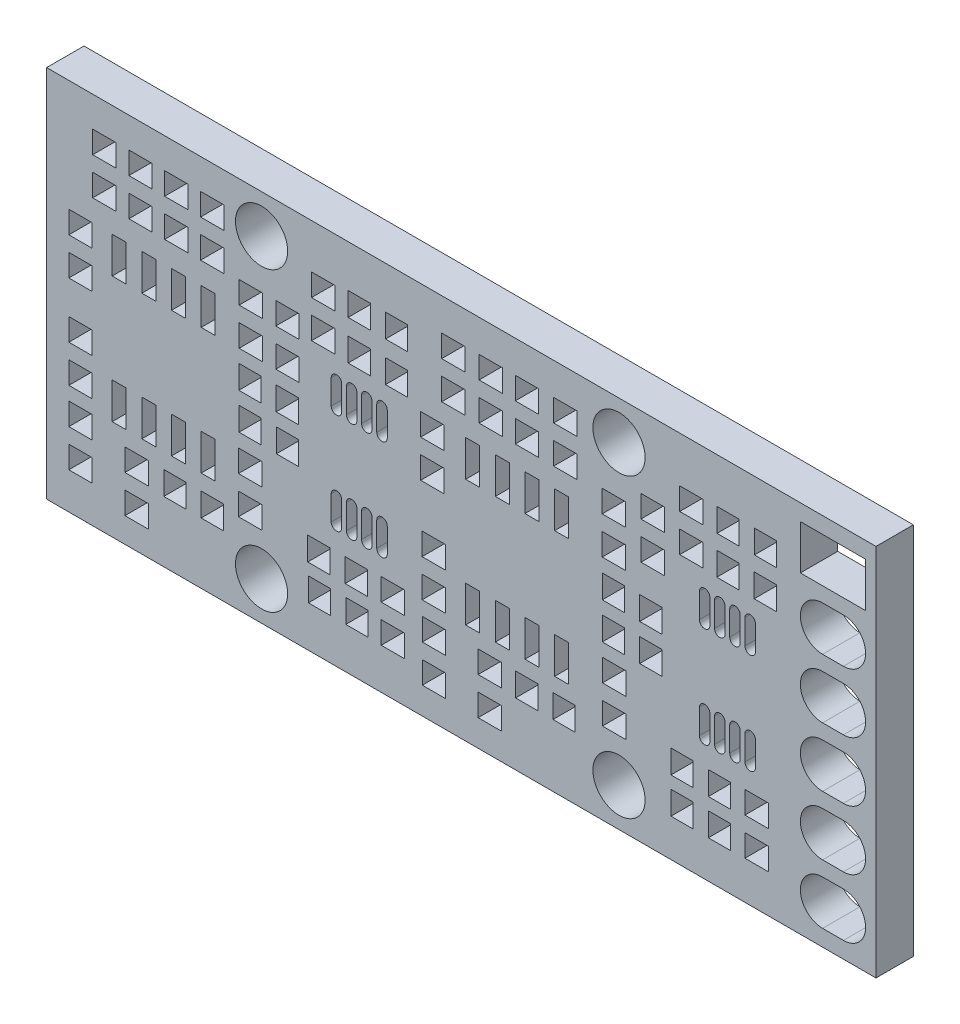
SolidWorks part; units mm, degrees
ref_plane "Plan de face" through (0, 0, 0) normal (0, 0, 1) x (1, 0, 0)
ref_plane "Plan de dessus" through (0, 0, 0) normal (0, 1, 0) x (1, 0, 0)
ref_plane "Plan de droite" through (0, 0, 0) normal (1, 0, 0) x (0, 0, -1)
sketch "Model" plane through (0, 0, 0) normal (0, 0, 1) x (1, 0, 0)
  line L0 (-3.237, -0.6975) -> (-0.443, -0.6975)
  line L1 (-0.443, -0.6975) -> (-0.443, -2.6025)
  line L2 (-0.443, -2.6025) -> (-3.237, -2.6025)
  line L3 (-3.237, -2.6025) -> (-3.237, -0.6975)
  line L4 (-1.3955, -5.1425) -> (-2.2845, -5.1425)
  line L5 (-2.2845, -3.2375) -> (-1.3955, -3.2375)
  line L6 (-1.3955, -7.6825) -> (-2.2845, -7.6825)
  line L7 (-2.2845, -5.7775) -> (-1.3955, -5.7775)
  line L8 (-1.3955, -10.2225) -> (-2.2845, -10.2225)
  line L9 (-2.2845, -8.3175) -> (-1.3955, -8.3175)
  line L10 (-1.3955, -12.7625) -> (-2.2845, -12.7625)
  line L11 (-2.2845, -10.8575) -> (-1.3955, -10.8575)
  line L12 (-1.3955, -15.3025) -> (-2.2845, -15.3025)
  line L13 (-2.2845, -13.3975) -> (-1.3955, -13.3975)
  line L14 (-22.87, -9.705) -> (-22.87, -10.755)
  line L15 (-23.32, -10.755) -> (-23.32, -9.705)
  line L16 (-22.22, -9.705) -> (-22.22, -10.755)
  line L17 (-22.67, -10.755) -> (-22.67, -9.705)
  line L18 (-21.57, -9.705) -> (-21.57, -10.755)
  line L19 (-22.02, -10.755) -> (-22.02, -9.705)
  line L20 (-20.92, -9.705) -> (-20.92, -10.755)
  line L21 (-21.37, -10.755) -> (-21.37, -9.705)
  line L22 (-20.92, -5.405) -> (-20.92, -6.455)
  line L23 (-21.37, -6.455) -> (-21.37, -5.405)
  line L24 (-21.57, -5.405) -> (-21.57, -6.455)
  line L25 (-22.02, -6.455) -> (-22.02, -5.405)
  line L26 (-22.22, -5.405) -> (-22.22, -6.455)
  line L27 (-22.67, -6.455) -> (-22.67, -5.405)
  line L28 (-22.87, -5.405) -> (-22.87, -6.455)
  line L29 (-23.32, -6.455) -> (-23.32, -5.405)
  line L30 (-7.11, -9.745) -> (-7.11, -10.795)
  line L31 (-7.56, -10.795) -> (-7.56, -9.745)
  line L32 (-6.46, -9.745) -> (-6.46, -10.795)
  line L33 (-6.91, -10.795) -> (-6.91, -9.745)
  line L34 (-5.81, -9.745) -> (-5.81, -10.795)
  line L35 (-6.26, -10.795) -> (-6.26, -9.745)
  line L36 (-5.16, -9.745) -> (-5.16, -10.795)
  line L37 (-5.61, -10.795) -> (-5.61, -9.745)
  line L38 (-5.16, -5.445) -> (-5.16, -6.495)
  line L39 (-5.61, -6.495) -> (-5.61, -5.445)
  line L40 (-5.81, -5.445) -> (-5.81, -6.495)
  line L41 (-6.26, -6.495) -> (-6.26, -5.445)
  line L42 (-6.46, -5.445) -> (-6.46, -6.495)
  line L43 (-6.91, -6.495) -> (-6.91, -5.445)
  line L44 (-7.11, -5.445) -> (-7.11, -6.495)
  line L45 (-7.56, -6.495) -> (-7.56, -5.445)
  line L46 (-28.885, -4.775) -> (-28.285, -4.775)
  line L47 (-28.285, -4.775) -> (-28.285, -6.325)
  line L48 (-28.285, -6.325) -> (-28.885, -6.325)
  line L49 (-28.885, -6.325) -> (-28.885, -4.775)
  line L50 (-30.155, -4.775) -> (-29.555, -4.775)
  line L51 (-29.555, -4.775) -> (-29.555, -6.325)
  line L52 (-29.555, -6.325) -> (-30.155, -6.325)
  line L53 (-30.155, -6.325) -> (-30.155, -4.775)
  line L54 (-31.425, -4.775) -> (-30.825, -4.775)
  line L55 (-30.825, -4.775) -> (-30.825, -6.325)
  line L56 (-30.825, -6.325) -> (-31.425, -6.325)
  line L57 (-31.425, -6.325) -> (-31.425, -4.775)
  line L58 (-32.695, -4.775) -> (-32.095, -4.775)
  line L59 (-32.095, -4.775) -> (-32.095, -6.325)
  line L60 (-32.095, -6.325) -> (-32.695, -6.325)
  line L61 (-32.695, -6.325) -> (-32.695, -4.775)
  line L62 (-32.695, -10.175) -> (-32.095, -10.175)
  line L63 (-32.095, -10.175) -> (-32.095, -11.725)
  line L64 (-32.095, -11.725) -> (-32.695, -11.725)
  line L65 (-32.695, -11.725) -> (-32.695, -10.175)
  line L66 (-31.425, -10.175) -> (-30.825, -10.175)
  line L67 (-30.825, -10.175) -> (-30.825, -11.725)
  line L68 (-30.825, -11.725) -> (-31.425, -11.725)
  line L69 (-31.425, -11.725) -> (-31.425, -10.175)
  line L70 (-30.155, -10.175) -> (-29.555, -10.175)
  line L71 (-29.555, -10.175) -> (-29.555, -11.725)
  line L72 (-29.555, -11.725) -> (-30.155, -11.725)
  line L73 (-30.155, -11.725) -> (-30.155, -10.175)
  line L74 (-28.885, -10.175) -> (-28.285, -10.175)
  line L75 (-28.285, -10.175) -> (-28.285, -11.725)
  line L76 (-28.285, -11.725) -> (-28.885, -11.725)
  line L77 (-28.885, -11.725) -> (-28.885, -10.175)
  line L78 (-13.755, -4.745) -> (-13.155, -4.745)
  line L79 (-13.155, -4.745) -> (-13.155, -6.295)
  line L80 (-13.155, -6.295) -> (-13.755, -6.295)
  line L81 (-13.755, -6.295) -> (-13.755, -4.745)
  line L82 (-15.025, -4.745) -> (-14.425, -4.745)
  line L83 (-14.425, -4.745) -> (-14.425, -6.295)
  line L84 (-14.425, -6.295) -> (-15.025, -6.295)
  line L85 (-15.025, -6.295) -> (-15.025, -4.745)
  line L86 (-16.295, -4.745) -> (-15.695, -4.745)
  line L87 (-15.695, -4.745) -> (-15.695, -6.295)
  line L88 (-15.695, -6.295) -> (-16.295, -6.295)
  line L89 (-16.295, -6.295) -> (-16.295, -4.745)
  line L90 (-17.565, -4.745) -> (-16.965, -4.745)
  line L91 (-16.965, -4.745) -> (-16.965, -6.295)
  line L92 (-16.965, -6.295) -> (-17.565, -6.295)
  line L93 (-17.565, -6.295) -> (-17.565, -4.745)
  line L94 (-17.565, -10.145) -> (-16.965, -10.145)
  line L95 (-16.965, -10.145) -> (-16.965, -11.695)
  line L96 (-16.965, -11.695) -> (-17.565, -11.695)
  line L97 (-17.565, -11.695) -> (-17.565, -10.145)
  line L98 (-16.295, -10.145) -> (-15.695, -10.145)
  line L99 (-15.695, -10.145) -> (-15.695, -11.695)
  line L100 (-15.695, -11.695) -> (-16.295, -11.695)
  line L101 (-16.295, -11.695) -> (-16.295, -10.145)
  line L102 (-15.025, -10.145) -> (-14.425, -10.145)
  line L103 (-14.425, -10.145) -> (-14.425, -11.695)
  line L104 (-14.425, -11.695) -> (-15.025, -11.695)
  line L105 (-15.025, -11.695) -> (-15.025, -10.145)
  line L106 (-13.755, -10.145) -> (-13.155, -10.145)
  line L107 (-13.155, -10.145) -> (-13.155, -11.695)
  line L108 (-13.155, -11.695) -> (-13.755, -11.695)
  line L109 (-13.755, -11.695) -> (-13.755, -10.145)
  line L110 (-23.375, -12.74) -> (-24.325, -12.74)
  line L111 (-24.325, -12.74) -> (-24.325, -11.74)
  line L112 (-24.325, -11.74) -> (-23.375, -11.74)
  line L113 (-23.375, -11.74) -> (-23.375, -12.74)
  line L114 (-21.775, -12.74) -> (-22.725, -12.74)
  line L115 (-22.725, -12.74) -> (-22.725, -11.74)
  line L116 (-22.725, -11.74) -> (-21.775, -11.74)
  line L117 (-21.775, -11.74) -> (-21.775, -12.74)
  line L118 (-33.53, -2.245) -> (-33.53, -1.295)
  line L119 (-33.53, -1.295) -> (-32.53, -1.295)
  line L120 (-32.53, -1.295) -> (-32.53, -2.245)
  line L121 (-32.53, -2.245) -> (-33.53, -2.245)
  line L122 (-33.53, -3.845) -> (-33.53, -2.895)
  line L123 (-33.53, -2.895) -> (-32.53, -2.895)
  line L124 (-32.53, -2.895) -> (-32.53, -3.845)
  line L125 (-32.53, -3.845) -> (-33.53, -3.845)
  line L126 (-34.55, -9.705) -> (-34.55, -8.755)
  line L127 (-34.55, -8.755) -> (-33.55, -8.755)
  line L128 (-33.55, -8.755) -> (-33.55, -9.705)
  line L129 (-33.55, -9.705) -> (-34.55, -9.705)
  line L130 (-34.55, -11.305) -> (-34.55, -10.355)
  line L131 (-34.55, -10.355) -> (-33.55, -10.355)
  line L132 (-33.55, -10.355) -> (-33.55, -11.305)
  line L133 (-33.55, -11.305) -> (-34.55, -11.305)
  line L134 (-34.55, -12.835) -> (-34.55, -11.885)
  line L135 (-34.55, -11.885) -> (-33.55, -11.885)
  line L136 (-33.55, -11.885) -> (-33.55, -12.835)
  line L137 (-33.55, -12.835) -> (-34.55, -12.835)
  line L138 (-34.55, -14.435) -> (-34.55, -13.485)
  line L139 (-34.55, -13.485) -> (-33.55, -13.485)
  line L140 (-33.55, -13.485) -> (-33.55, -14.435)
  line L141 (-33.55, -14.435) -> (-34.55, -14.435)
  line L142 (-26.315, -9.4) -> (-27.265, -9.4)
  line L143 (-27.265, -9.4) -> (-27.265, -8.4)
  line L144 (-27.265, -8.4) -> (-26.315, -8.4)
  line L145 (-26.315, -8.4) -> (-26.315, -9.4)
  line L146 (-24.715, -9.4) -> (-25.665, -9.4)
  line L147 (-25.665, -9.4) -> (-25.665, -8.4)
  line L148 (-25.665, -8.4) -> (-24.715, -8.4)
  line L149 (-24.715, -8.4) -> (-24.715, -9.4)
  line L150 (-32.15, -13.335) -> (-32.15, -12.385)
  line L151 (-32.15, -12.385) -> (-31.15, -12.385)
  line L152 (-31.15, -12.385) -> (-31.15, -13.335)
  line L153 (-31.15, -13.335) -> (-32.15, -13.335)
  line L154 (-32.15, -14.935) -> (-32.15, -13.985)
  line L155 (-32.15, -13.985) -> (-31.15, -13.985)
  line L156 (-31.15, -13.985) -> (-31.15, -14.935)
  line L157 (-31.15, -14.935) -> (-32.15, -14.935)
  line L158 (-26.325, -7.85) -> (-27.275, -7.85)
  line L159 (-27.275, -7.85) -> (-27.275, -6.85)
  line L160 (-27.275, -6.85) -> (-26.325, -6.85)
  line L161 (-26.325, -6.85) -> (-26.325, -7.85)
  line L162 (-24.725, -7.85) -> (-25.675, -7.85)
  line L163 (-25.675, -7.85) -> (-25.675, -6.85)
  line L164 (-25.675, -6.85) -> (-24.725, -6.85)
  line L165 (-24.725, -6.85) -> (-24.725, -7.85)
  line L166 (-34.55, -5.725) -> (-34.55, -4.775)
  line L167 (-34.55, -4.775) -> (-33.55, -4.775)
  line L168 (-33.55, -4.775) -> (-33.55, -5.725)
  line L169 (-33.55, -5.725) -> (-34.55, -5.725)
  line L170 (-34.55, -7.325) -> (-34.55, -6.375)
  line L171 (-34.55, -6.375) -> (-33.55, -6.375)
  line L172 (-33.55, -6.375) -> (-33.55, -7.325)
  line L173 (-33.55, -7.325) -> (-34.55, -7.325)
  line L174 (-28.885, -12.39) -> (-27.935, -12.39)
  line L175 (-27.935, -12.39) -> (-27.935, -13.39)
  line L176 (-27.935, -13.39) -> (-28.885, -13.39)
  line L177 (-28.885, -13.39) -> (-28.885, -12.39)
  line L178 (-30.485, -12.39) -> (-29.535, -12.39)
  line L179 (-29.535, -12.39) -> (-29.535, -13.39)
  line L180 (-29.535, -13.39) -> (-30.485, -13.39)
  line L181 (-30.485, -13.39) -> (-30.485, -12.39)
  line L182 (-21.645, -4.5) -> (-22.595, -4.5)
  line L183 (-22.595, -4.5) -> (-22.595, -3.5)
  line L184 (-22.595, -3.5) -> (-21.645, -3.5)
  line L185 (-21.645, -3.5) -> (-21.645, -4.5)
  line L186 (-20.045, -4.5) -> (-20.995, -4.5)
  line L187 (-20.995, -4.5) -> (-20.995, -3.5)
  line L188 (-20.995, -3.5) -> (-20.045, -3.5)
  line L189 (-20.045, -3.5) -> (-20.045, -4.5)
  line L190 (-30.45, -2.245) -> (-30.45, -1.295)
  line L191 (-30.45, -1.295) -> (-29.45, -1.295)
  line L192 (-29.45, -1.295) -> (-29.45, -2.245)
  line L193 (-29.45, -2.245) -> (-30.45, -2.245)
  line L194 (-30.45, -3.845) -> (-30.45, -2.895)
  line L195 (-30.45, -2.895) -> (-29.45, -2.895)
  line L196 (-29.45, -2.895) -> (-29.45, -3.845)
  line L197 (-29.45, -3.845) -> (-30.45, -3.845)
  line L198 (-24.69, -5.325) -> (-24.69, -6.275)
  line L199 (-24.69, -6.275) -> (-25.69, -6.275)
  line L200 (-25.69, -6.275) -> (-25.69, -5.325)
  line L201 (-25.69, -5.325) -> (-24.69, -5.325)
  line L202 (-24.69, -3.725) -> (-24.69, -4.675)
  line L203 (-24.69, -4.675) -> (-25.69, -4.675)
  line L204 (-25.69, -4.675) -> (-25.69, -3.725)
  line L205 (-25.69, -3.725) -> (-24.69, -3.725)
  line L206 (-27.91, -2.895) -> (-27.91, -3.845)
  line L207 (-27.91, -3.845) -> (-28.91, -3.845)
  line L208 (-28.91, -3.845) -> (-28.91, -2.895)
  line L209 (-28.91, -2.895) -> (-27.91, -2.895)
  line L210 (-27.91, -1.295) -> (-27.91, -2.245)
  line L211 (-27.91, -2.245) -> (-28.91, -2.245)
  line L212 (-28.91, -2.245) -> (-28.91, -1.295)
  line L213 (-28.91, -1.295) -> (-27.91, -1.295)
  line L214 (-7.825, -12.86) -> (-8.775, -12.86)
  line L215 (-8.775, -12.86) -> (-8.775, -11.86)
  line L216 (-8.775, -11.86) -> (-7.825, -11.86)
  line L217 (-7.825, -11.86) -> (-7.825, -12.86)
  line L218 (-6.225, -12.86) -> (-7.175, -12.86)
  line L219 (-7.175, -12.86) -> (-7.175, -11.86)
  line L220 (-7.175, -11.86) -> (-6.225, -11.86)
  line L221 (-6.225, -11.86) -> (-6.225, -12.86)
  line L222 (-18.59, -2.335) -> (-18.59, -1.385)
  line L223 (-18.59, -1.385) -> (-17.59, -1.385)
  line L224 (-17.59, -1.385) -> (-17.59, -2.335)
  line L225 (-17.59, -2.335) -> (-18.59, -2.335)
  line L226 (-18.59, -3.935) -> (-18.59, -2.985)
  line L227 (-18.59, -2.985) -> (-17.59, -2.985)
  line L228 (-17.59, -2.985) -> (-17.59, -3.935)
  line L229 (-17.59, -3.935) -> (-18.59, -3.935)
  line L230 (-19.43, -10.095) -> (-19.43, -9.145)
  line L231 (-19.43, -9.145) -> (-18.43, -9.145)
  line L232 (-18.43, -9.145) -> (-18.43, -10.095)
  line L233 (-18.43, -10.095) -> (-19.43, -10.095)
  line L234 (-19.43, -11.695) -> (-19.43, -10.745)
  line L235 (-19.43, -10.745) -> (-18.43, -10.745)
  line L236 (-18.43, -10.745) -> (-18.43, -11.695)
  line L237 (-18.43, -11.695) -> (-19.43, -11.695)
  line L238 (-19.42, -13.255) -> (-19.42, -12.305)
  line L239 (-19.42, -12.305) -> (-18.42, -12.305)
  line L240 (-18.42, -12.305) -> (-18.42, -13.255)
  line L241 (-18.42, -13.255) -> (-19.42, -13.255)
  line L242 (-19.42, -14.855) -> (-19.42, -13.905)
  line L243 (-19.42, -13.905) -> (-18.42, -13.905)
  line L244 (-18.42, -13.905) -> (-18.42, -14.855)
  line L245 (-18.42, -14.855) -> (-19.42, -14.855)
  line L246 (-10.765, -9.4) -> (-11.715, -9.4)
  line L247 (-11.715, -9.4) -> (-11.715, -8.4)
  line L248 (-11.715, -8.4) -> (-10.765, -8.4)
  line L249 (-10.765, -8.4) -> (-10.765, -9.4)
  line L250 (-9.165, -9.4) -> (-10.115, -9.4)
  line L251 (-10.115, -9.4) -> (-10.115, -8.4)
  line L252 (-10.115, -8.4) -> (-9.165, -8.4)
  line L253 (-9.165, -8.4) -> (-9.165, -9.4)
  line L254 (-17.03, -13.265) -> (-17.03, -12.315)
  line L255 (-17.03, -12.315) -> (-16.03, -12.315)
  line L256 (-16.03, -12.315) -> (-16.03, -13.265)
  line L257 (-16.03, -13.265) -> (-17.03, -13.265)
  line L258 (-17.03, -14.865) -> (-17.03, -13.915)
  line L259 (-17.03, -13.915) -> (-16.03, -13.915)
  line L260 (-16.03, -13.915) -> (-16.03, -14.865)
  line L261 (-16.03, -14.865) -> (-17.03, -14.865)
  line L262 (-10.765, -7.84) -> (-11.715, -7.84)
  line L263 (-11.715, -7.84) -> (-11.715, -6.84)
  line L264 (-11.715, -6.84) -> (-10.765, -6.84)
  line L265 (-10.765, -6.84) -> (-10.765, -7.84)
  line L266 (-9.165, -7.84) -> (-10.115, -7.84)
  line L267 (-10.115, -7.84) -> (-10.115, -6.84)
  line L268 (-10.115, -6.84) -> (-9.165, -6.84)
  line L269 (-9.165, -6.84) -> (-9.165, -7.84)
  line L270 (-19.49, -5.695) -> (-19.49, -4.745)
  line L271 (-19.49, -4.745) -> (-18.49, -4.745)
  line L272 (-18.49, -4.745) -> (-18.49, -5.695)
  line L273 (-18.49, -5.695) -> (-19.49, -5.695)
  line L274 (-19.49, -7.295) -> (-19.49, -6.345)
  line L275 (-19.49, -6.345) -> (-18.49, -6.345)
  line L276 (-18.49, -6.345) -> (-18.49, -7.295)
  line L277 (-18.49, -7.295) -> (-19.49, -7.295)
  line L278 (-13.825, -12.33) -> (-12.875, -12.33)
  line L279 (-12.875, -12.33) -> (-12.875, -13.33)
  line L280 (-12.875, -13.33) -> (-13.825, -13.33)
  line L281 (-13.825, -13.33) -> (-13.825, -12.33)
  line L282 (-15.425, -12.33) -> (-14.475, -12.33)
  line L283 (-14.475, -12.33) -> (-14.475, -13.33)
  line L284 (-14.475, -13.33) -> (-15.425, -13.33)
  line L285 (-15.425, -13.33) -> (-15.425, -12.33)
  line L286 (-5.865, -4.55) -> (-6.815, -4.55)
  line L287 (-6.815, -4.55) -> (-6.815, -3.55)
  line L288 (-6.815, -3.55) -> (-5.865, -3.55)
  line L289 (-5.865, -3.55) -> (-5.865, -4.55)
  line L290 (-4.265, -4.55) -> (-5.215, -4.55)
  line L291 (-5.215, -4.55) -> (-5.215, -3.55)
  line L292 (-5.215, -3.55) -> (-4.265, -3.55)
  line L293 (-4.265, -3.55) -> (-4.265, -4.55)
  line L294 (-15.44, -2.325) -> (-15.44, -1.375)
  line L295 (-15.44, -1.375) -> (-14.44, -1.375)
  line L296 (-14.44, -1.375) -> (-14.44, -2.325)
  line L297 (-14.44, -2.325) -> (-15.44, -2.325)
  line L298 (-15.44, -3.925) -> (-15.44, -2.975)
  line L299 (-15.44, -2.975) -> (-14.44, -2.975)
  line L300 (-14.44, -2.975) -> (-14.44, -3.925)
  line L301 (-14.44, -3.925) -> (-15.44, -3.925)
  line L302 (-9.06, -4.665) -> (-9.06, -5.615)
  line L303 (-9.06, -5.615) -> (-10.06, -5.615)
  line L304 (-10.06, -5.615) -> (-10.06, -4.665)
  line L305 (-10.06, -4.665) -> (-9.06, -4.665)
  line L306 (-9.06, -3.065) -> (-9.06, -4.015)
  line L307 (-9.06, -4.015) -> (-10.06, -4.015)
  line L308 (-10.06, -4.015) -> (-10.06, -3.065)
  line L309 (-10.06, -3.065) -> (-9.06, -3.065)
  line L310 (-12.8, -2.975) -> (-12.8, -3.925)
  line L311 (-12.8, -3.925) -> (-13.8, -3.925)
  line L312 (-13.8, -3.925) -> (-13.8, -2.975)
  line L313 (-13.8, -2.975) -> (-12.8, -2.975)
  line L314 (-12.8, -1.375) -> (-12.8, -2.325)
  line L315 (-12.8, -2.325) -> (-13.8, -2.325)
  line L316 (-13.8, -2.325) -> (-13.8, -1.375)
  line L317 (-13.8, -1.375) -> (-12.8, -1.375)
  line L318 (-22.695, -13.24) -> (-21.745, -13.24)
  line L319 (-21.745, -13.24) -> (-21.745, -14.24)
  line L320 (-21.745, -14.24) -> (-22.695, -14.24)
  line L321 (-22.695, -14.24) -> (-22.695, -13.24)
  line L322 (-24.295, -13.24) -> (-23.345, -13.24)
  line L323 (-23.345, -13.24) -> (-23.345, -14.24)
  line L324 (-23.345, -14.24) -> (-24.295, -14.24)
  line L325 (-24.295, -14.24) -> (-24.295, -13.24)
  line L326 (-27.29, -10.945) -> (-27.29, -9.995)
  line L327 (-27.29, -9.995) -> (-26.29, -9.995)
  line L328 (-26.29, -9.995) -> (-26.29, -10.945)
  line L329 (-26.29, -10.945) -> (-27.29, -10.945)
  line L330 (-27.29, -12.545) -> (-27.29, -11.595)
  line L331 (-27.29, -11.595) -> (-26.29, -11.595)
  line L332 (-26.29, -11.595) -> (-26.29, -12.545)
  line L333 (-26.29, -12.545) -> (-27.29, -12.545)
  line L334 (-26.26, -5.335) -> (-26.26, -6.285)
  line L335 (-26.26, -6.285) -> (-27.26, -6.285)
  line L336 (-27.26, -6.285) -> (-27.26, -5.335)
  line L337 (-27.26, -5.335) -> (-26.26, -5.335)
  line L338 (-26.26, -3.735) -> (-26.26, -4.685)
  line L339 (-26.26, -4.685) -> (-27.26, -4.685)
  line L340 (-27.26, -4.685) -> (-27.26, -3.735)
  line L341 (-27.26, -3.735) -> (-26.26, -3.735)
  line L342 (-24.16, -2.855) -> (-24.16, -1.905)
  line L343 (-24.16, -1.905) -> (-23.16, -1.905)
  line L344 (-23.16, -1.905) -> (-23.16, -2.855)
  line L345 (-23.16, -2.855) -> (-24.16, -2.855)
  line L346 (-24.16, -4.455) -> (-24.16, -3.505)
  line L347 (-24.16, -3.505) -> (-23.16, -3.505)
  line L348 (-23.16, -3.505) -> (-23.16, -4.455)
  line L349 (-23.16, -4.455) -> (-24.16, -4.455)
  line L350 (-21.645, -2.81) -> (-22.595, -2.81)
  line L351 (-22.595, -2.81) -> (-22.595, -1.81)
  line L352 (-22.595, -1.81) -> (-21.645, -1.81)
  line L353 (-21.645, -1.81) -> (-21.645, -2.81)
  line L354 (-20.045, -2.81) -> (-20.995, -2.81)
  line L355 (-20.995, -2.81) -> (-20.995, -1.81)
  line L356 (-20.995, -1.81) -> (-20.045, -1.81)
  line L357 (-20.045, -1.81) -> (-20.045, -2.81)
  line L358 (-21.18, -12.655) -> (-21.18, -11.705)
  line L359 (-21.18, -11.705) -> (-20.18, -11.705)
  line L360 (-20.18, -11.705) -> (-20.18, -12.655)
  line L361 (-20.18, -12.655) -> (-21.18, -12.655)
  line L362 (-21.18, -14.255) -> (-21.18, -13.305)
  line L363 (-21.18, -13.305) -> (-20.18, -13.305)
  line L364 (-20.18, -13.305) -> (-20.18, -14.255)
  line L365 (-20.18, -14.255) -> (-21.18, -14.255)
  line L366 (-30.98, -2.895) -> (-30.98, -3.845)
  line L367 (-30.98, -3.845) -> (-31.98, -3.845)
  line L368 (-31.98, -3.845) -> (-31.98, -2.895)
  line L369 (-31.98, -2.895) -> (-30.98, -2.895)
  line L370 (-30.98, -1.295) -> (-30.98, -2.245)
  line L371 (-30.98, -2.245) -> (-31.98, -2.245)
  line L372 (-31.98, -2.245) -> (-31.98, -1.295)
  line L373 (-31.98, -1.295) -> (-30.98, -1.295)
  line L374 (-7.175, -13.39) -> (-6.225, -13.39)
  line L375 (-6.225, -13.39) -> (-6.225, -14.39)
  line L376 (-6.225, -14.39) -> (-7.175, -14.39)
  line L377 (-7.175, -14.39) -> (-7.175, -13.39)
  line L378 (-8.775, -13.39) -> (-7.825, -13.39)
  line L379 (-7.825, -13.39) -> (-7.825, -14.39)
  line L380 (-7.825, -14.39) -> (-8.775, -14.39)
  line L381 (-8.775, -14.39) -> (-8.775, -13.39)
  line L382 (-11.71, -10.915) -> (-11.71, -9.965)
  line L383 (-11.71, -9.965) -> (-10.71, -9.965)
  line L384 (-10.71, -9.965) -> (-10.71, -10.915)
  line L385 (-10.71, -10.915) -> (-11.71, -10.915)
  line L386 (-11.71, -12.515) -> (-11.71, -11.565)
  line L387 (-11.71, -11.565) -> (-10.71, -11.565)
  line L388 (-10.71, -11.565) -> (-10.71, -12.515)
  line L389 (-10.71, -12.515) -> (-11.71, -12.515)
  line L390 (-10.72, -5.305) -> (-10.72, -6.255)
  line L391 (-10.72, -6.255) -> (-11.72, -6.255)
  line L392 (-11.72, -6.255) -> (-11.72, -5.305)
  line L393 (-11.72, -5.305) -> (-10.72, -5.305)
  line L394 (-10.72, -3.705) -> (-10.72, -4.655)
  line L395 (-10.72, -4.655) -> (-11.72, -4.655)
  line L396 (-11.72, -4.655) -> (-11.72, -3.705)
  line L397 (-11.72, -3.705) -> (-10.72, -3.705)
  line L398 (-8.4, -2.905) -> (-8.4, -1.955)
  line L399 (-8.4, -1.955) -> (-7.4, -1.955)
  line L400 (-7.4, -1.955) -> (-7.4, -2.905)
  line L401 (-7.4, -2.905) -> (-8.4, -2.905)
  line L402 (-8.4, -4.505) -> (-8.4, -3.555)
  line L403 (-8.4, -3.555) -> (-7.4, -3.555)
  line L404 (-7.4, -3.555) -> (-7.4, -4.505)
  line L405 (-7.4, -4.505) -> (-8.4, -4.505)
  line L406 (-5.855, -2.92) -> (-6.805, -2.92)
  line L407 (-6.805, -2.92) -> (-6.805, -1.92)
  line L408 (-6.805, -1.92) -> (-5.855, -1.92)
  line L409 (-5.855, -1.92) -> (-5.855, -2.92)
  line L410 (-4.255, -2.92) -> (-5.205, -2.92)
  line L411 (-5.205, -2.92) -> (-5.205, -1.92)
  line L412 (-5.205, -1.92) -> (-4.255, -1.92)
  line L413 (-4.255, -1.92) -> (-4.255, -2.92)
  line L414 (-5.61, -12.765) -> (-5.61, -11.815)
  line L415 (-5.61, -11.815) -> (-4.61, -11.815)
  line L416 (-4.61, -11.815) -> (-4.61, -12.765)
  line L417 (-4.61, -12.765) -> (-5.61, -12.765)
  line L418 (-5.61, -14.365) -> (-5.61, -13.415)
  line L419 (-5.61, -13.415) -> (-4.61, -13.415)
  line L420 (-4.61, -13.415) -> (-4.61, -14.365)
  line L421 (-4.61, -14.365) -> (-5.61, -14.365)
  line L422 (-15.99, -2.975) -> (-15.99, -3.925)
  line L423 (-15.99, -3.925) -> (-16.99, -3.925)
  line L424 (-16.99, -3.925) -> (-16.99, -2.975)
  line L425 (-16.99, -2.975) -> (-15.99, -2.975)
  line L426 (-15.99, -1.375) -> (-15.99, -2.325)
  line L427 (-15.99, -2.325) -> (-16.99, -2.325)
  line L428 (-16.99, -2.325) -> (-16.99, -1.375)
  line L429 (-16.99, -1.375) -> (-15.99, -1.375)
  line L430 (0, -11.02) -> (0, 0)
  line L431 (0, 0) -> (-25, 0)
  line L432 (-25, 0) -> (-35.5, 0)
  line L433 (-35.5, 0) -> (-35.5, -16)
  line L434 (-35.5, -16) -> (-25, -16)
  line L435 (-25, -16) -> (0, -16)
  line L436 (0, -16) -> (0, -11.02)
  circle A0 centre (-26.3, -14.35) radius 1.1176
  circle A1 centre (-11, -14.35) radius 1.1176
  circle A2 centre (-26.3, -1.65) radius 1.1176
  circle A3 centre (-11, -1.65) radius 1.1176
  arc A4 (-2.2845, -3.2375) -> (-2.2845, -5.1425) centre (-2.2845, -4.19) ccw
  arc A5 (-1.3955, -5.1425) -> (-1.3955, -3.2375) centre (-1.3955, -4.19) ccw
  arc A6 (-2.2845, -5.7775) -> (-2.2845, -7.6825) centre (-2.2845, -6.73) ccw
  arc A7 (-1.3955, -7.6825) -> (-1.3955, -5.7775) centre (-1.3955, -6.73) ccw
  arc A8 (-2.2845, -8.3175) -> (-2.2845, -10.2225) centre (-2.2845, -9.27) ccw
  arc A9 (-1.3955, -10.2225) -> (-1.3955, -8.3175) centre (-1.3955, -9.27) ccw
  arc A10 (-2.2845, -10.8575) -> (-2.2845, -12.7625) centre (-2.2845, -11.81) ccw
  arc A11 (-1.3955, -12.7625) -> (-1.3955, -10.8575) centre (-1.3955, -11.81) ccw
  arc A12 (-2.2845, -13.3975) -> (-2.2845, -15.3025) centre (-2.2845, -14.35) ccw
  arc A13 (-1.3955, -15.3025) -> (-1.3955, -13.3975) centre (-1.3955, -14.35) ccw
  arc A14 (-23.32, -10.755) -> (-22.87, -10.755) centre (-23.095, -10.755) ccw
  arc A15 (-22.87, -9.705) -> (-23.32, -9.705) centre (-23.095, -9.705) ccw
  arc A16 (-22.67, -10.755) -> (-22.22, -10.755) centre (-22.445, -10.755) ccw
  arc A17 (-22.22, -9.705) -> (-22.67, -9.705) centre (-22.445, -9.705) ccw
  arc A18 (-22.02, -10.755) -> (-21.57, -10.755) centre (-21.795, -10.755) ccw
  arc A19 (-21.57, -9.705) -> (-22.02, -9.705) centre (-21.795, -9.705) ccw
  arc A20 (-21.37, -10.755) -> (-20.92, -10.755) centre (-21.145, -10.755) ccw
  arc A21 (-20.92, -9.705) -> (-21.37, -9.705) centre (-21.145, -9.705) ccw
  arc A22 (-21.37, -6.455) -> (-20.92, -6.455) centre (-21.145, -6.455) ccw
  arc A23 (-20.92, -5.405) -> (-21.37, -5.405) centre (-21.145, -5.405) ccw
  arc A24 (-22.02, -6.455) -> (-21.57, -6.455) centre (-21.795, -6.455) ccw
  arc A25 (-21.57, -5.405) -> (-22.02, -5.405) centre (-21.795, -5.405) ccw
  arc A26 (-22.67, -6.455) -> (-22.22, -6.455) centre (-22.445, -6.455) ccw
  arc A27 (-22.22, -5.405) -> (-22.67, -5.405) centre (-22.445, -5.405) ccw
  arc A28 (-23.32, -6.455) -> (-22.87, -6.455) centre (-23.095, -6.455) ccw
  arc A29 (-22.87, -5.405) -> (-23.32, -5.405) centre (-23.095, -5.405) ccw
  arc A30 (-7.56, -10.795) -> (-7.11, -10.795) centre (-7.335, -10.795) ccw
  arc A31 (-7.11, -9.745) -> (-7.56, -9.745) centre (-7.335, -9.745) ccw
  arc A32 (-6.91, -10.795) -> (-6.46, -10.795) centre (-6.685, -10.795) ccw
  arc A33 (-6.46, -9.745) -> (-6.91, -9.745) centre (-6.685, -9.745) ccw
  arc A34 (-6.26, -10.795) -> (-5.81, -10.795) centre (-6.035, -10.795) ccw
  arc A35 (-5.81, -9.745) -> (-6.26, -9.745) centre (-6.035, -9.745) ccw
  arc A36 (-5.61, -10.795) -> (-5.16, -10.795) centre (-5.385, -10.795) ccw
  arc A37 (-5.16, -9.745) -> (-5.61, -9.745) centre (-5.385, -9.745) ccw
  arc A38 (-5.61, -6.495) -> (-5.16, -6.495) centre (-5.385, -6.495) ccw
  arc A39 (-5.16, -5.445) -> (-5.61, -5.445) centre (-5.385, -5.445) ccw
  arc A40 (-6.26, -6.495) -> (-5.81, -6.495) centre (-6.035, -6.495) ccw
  arc A41 (-5.81, -5.445) -> (-6.26, -5.445) centre (-6.035, -5.445) ccw
  arc A42 (-6.91, -6.495) -> (-6.46, -6.495) centre (-6.685, -6.495) ccw
  arc A43 (-6.46, -5.445) -> (-6.91, -5.445) centre (-6.685, -5.445) ccw
  arc A44 (-7.56, -6.495) -> (-7.11, -6.495) centre (-7.335, -6.495) ccw
  arc A45 (-7.11, -5.445) -> (-7.56, -5.445) centre (-7.335, -5.445) ccw
extrude "Boss.-Extru.1" add sketch "Model" along normal blind 1.6
